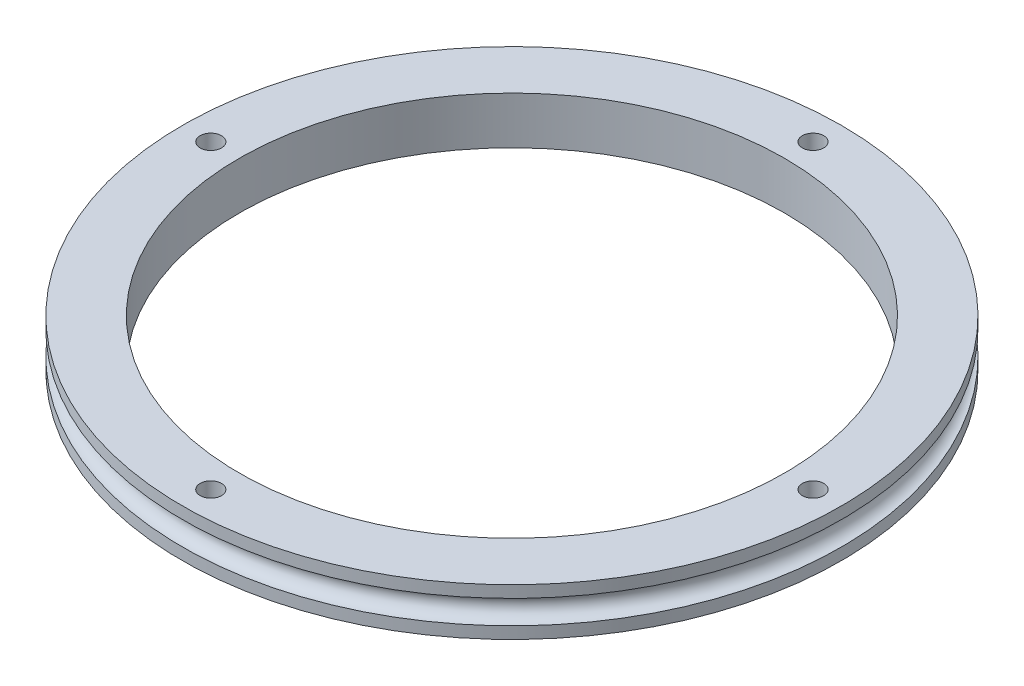
SolidWorks part; units mm, degrees
material "3003 Alloy"
ref_plane "Płaszczyzna przednia" through (0, 0, 0) normal (0, 0, 1) x (1, 0, 0)
ref_plane "Płaszczyzna górna" through (0, 0, 0) normal (0, 1, 0) x (1, 0, 0)
ref_plane "Płaszczyzna prawa" through (0, 0, 0) normal (1, 0, 0) x (0, 0, -1)
ref_axis "Axis1" through (0, -5.61, 0) along (0, 1, 0)
sketch "Sketch4" plane through (0, 0, 0) normal (0, 1, 0) x (1, 0, 0)
  line L0 (0, 0) -> (-69.5, 0) construction
  circle A0 centre (0, 0) radius 69.5 construction
sketch "Sketch1" plane through (0, 0, 0) normal (0, 0, 1) x (1, 0, 0)
  line L0 (-57.5, 5) -> (-57.5, -5)
  line L1 (-57.5, 5) -> (-69.5, 5)
  line L3 (-57.5, -5) -> (-69.5, -5)
  line L4 (-69.5, 5) -> (-69.5, 2.5)
  line L5 (-57.5, 5) -> (-69.5, -5) construction
  line L6 (-57.5, -5) -> (-69.5, 5) construction
  line L7 (-69.5, -2.5) -> (-69.5, -5)
  arc A2 (-69.5, 2.5) -> (-69.5, -2.5) centre (-69.5, 0) cw
  point P0 (-63.5, 0)
  dimension "D1" = 12
  dimension "D2" = 10
  dimension "D4" = 5
revolve "Revolve1" add sketch "Sketch1" angle 360 about axis through (0, -5.61, 0) along (0, 1, 0)
hole_wizard "CSK for M4 Countersunk Flat Head Screw1" positions "Sketch2" profile "Sketch3" countersink size "M4" standard "ISO" end condition through all
sketch "Sketch2" plane through (0, -5, 0) normal (0, -1, 0) x (-1, 0, 0)
  point P0 (63.5, 0)
sketch "Sketch3" plane through (-63.5, -5, 0) normal (1, 0, 0) x (0, 0, -1)
  line L0 (0, 0) -> (0, 10)
  line L1 (0, 10) -> (2.25, 10)
  line L2 (2.25, 10) -> (2.25, 2.45)
  line L3 (2.25, 2.45) -> (4.7, 0)
  line L5 (4.7, 0) -> (0, 0)
  line L6 (-2.25, 2.45) -> (-4.7, 0) construction
  line L11 (0, -6.35) -> (0, 107.95) construction
  dimension "Thru Hole Dia." = 4.5
  dimension "Thru Hole Depth" = 10
  dimension "Near C'Sink Dia." = 9.4
  dimension "Near C'Sink Angle" = 90
pattern_circular "CirPattern1" count 4 over 360 about axis through (0, 0, 0) along (0, 1, 0) of "CSK for M4 Countersunk Flat Head Screw1"
